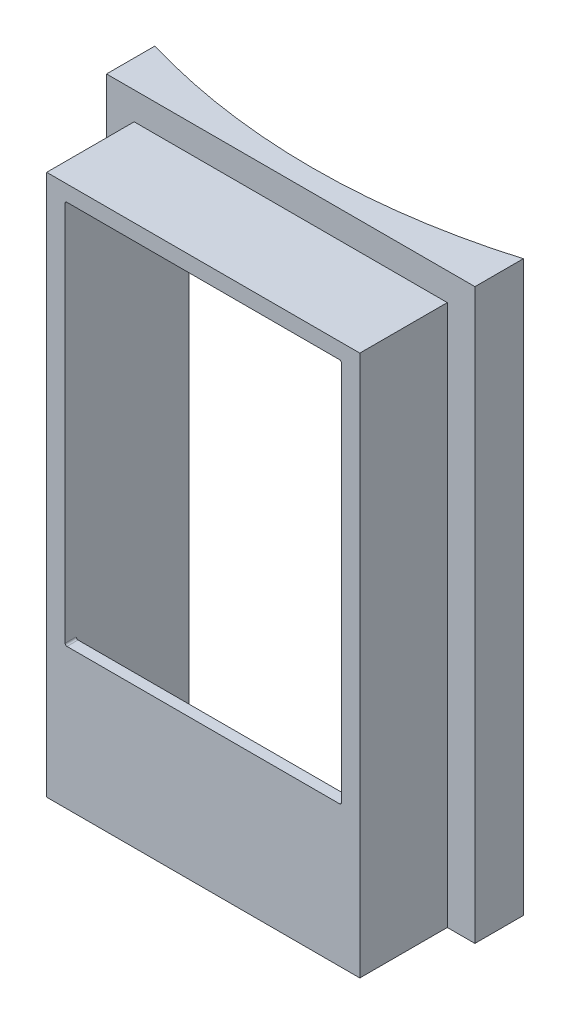
SolidWorks part; units mm, degrees
ref_plane "Front Plane" through (0, 0, 0) normal (0, 0, 1) x (1, 0, 0)
ref_plane "Top Plane" through (0, 0, 0) normal (0, 1, 0) x (1, 0, 0)
ref_plane "Right Plane" through (0, 0, 0) normal (1, 0, 0) x (0, 0, -1)
sketch "Sketch1" plane through (0, 0, 0) normal (0, 0, 1) x (1, 0, 0)
  line L1 (-63.5, 95.885) -> (63.5, 95.885)
  line L2 (-63.5, 95.885) -> (-63.5, -100.203)
  line L3 (-63.5, -100.203) -> (63.5, -100.203)
  line L4 (63.5, 95.885) -> (63.5, -100.203)
  point P5 (0, 95.885)
  dimension "D1" = 127
  dimension "D2" = 196.088
extrude "Extrude1" add sketch "Sketch1" along normal blind 230.2002
sketch "Sketch5" plane through (0, 0, 230.2002) normal (0, 0, 1) x (1, 0, 0)
  line L0 (63.5, 95.885) -> (-63.5, 95.885) construction
  line L1 (-53.975, 86.36) -> (53.975, 86.36)
  line L2 (-53.975, 86.36) -> (-53.975, -100.203)
  line L3 (-53.975, -100.203) -> (53.975, -100.203)
  line L4 (53.975, 86.36) -> (53.975, -100.203)
  line L5 (0, 95.885) -> (0, -100.203) construction
  line L8 (-63.5, -100.203) -> (63.5, -100.203) construction
  point P4 (0, -100.203)
  point P5 (0, 95.885)
  point P11 (0, 86.36)
  dimension "D1" = 107.95
  dimension "D2" = 9.525
extrude "Extrude4" add sketch "Sketch5" along normal blind 30.1523
sketch "Sketch2" plane through (0, 95.885, 0) normal (0, 1, 0) x (-1, 0, 0)
  line L0 (-63.5, 0) -> (63.5, 0) construction
  circle A1 centre (0, 0) radius 222.758
sketch "Sketch4" plane through (0, 0, 230.2002) normal (0, 0, 1) x (1, 0, 0)
  line L0 (53.975, 86.36) -> (-53.975, 86.36) construction
  line L1 (-47.625, 80.899) -> (47.625, 80.899)
  line L2 (-47.625, 80.899) -> (-47.625, -51.689)
  line L3 (-47.625, -51.689) -> (47.625, -51.689)
  line L4 (47.625, 80.899) -> (47.625, -51.689)
  point P4 (0, -51.689)
  point P5 (0, 80.899)
  point P6 (0, 0)
  dimension "D1" = 95.25
  dimension "D2" = 5.461
  dimension "D3" = 132.588
extrude "Extrude2" cut sketch "Sketch4" against normal blind 273.8502 and the other way blind 93.98
sketch "Sketch6" plane through (0, 0, 0) normal (0, 0, -1) x (-1, 0, 0)
  line L0 (-47.625, -51.689) -> (47.625, -51.689) construction
  line L1 (-47.625, -51.689) -> (47.625, -51.689)
  line L2 (-47.625, -51.689) -> (-47.625, -97.663)
  line L3 (-47.625, -97.663) -> (47.625, -97.663)
  line L4 (47.625, -51.689) -> (47.625, -97.663)
  line L6 (-47.625, 80.899) -> (47.625, 80.899)
  line L7 (-47.625, 80.899) -> (-47.625, 83.82)
  line L8 (-47.625, 83.82) -> (47.625, 83.82)
  line L9 (47.625, 80.899) -> (47.625, 83.82)
  line L10 (63.5, -100.203) -> (-63.5, -100.203) construction
  line L11 (-63.5, 95.885) -> (63.5, 95.885) construction
  point P4 (0, -100.203)
  point P6 (0, -51.689)
  point P13 (0, -100.203)
  point P15 (0, 95.885)
  point P19 (0, 80.899)
  point P22 (0, -97.663)
  dimension "D1" = 95.25
  dimension "D2" = 2.921
extrude "Extrude5" cut sketch "Sketch6" against normal blind 256.54
fillet "Fillet1" radius 2.54 4 edges at (-47.625, -97.663, 128.27) (47.625, -97.663, 128.27) (-47.625, 83.82, 128.27) (47.625, 83.82, 128.27)
extrude "Extrude3" cut sketch "Sketch2" against normal blind 202.86
sketch "Sketch7" plane through (0, 0, 260.3525) normal (0, 0, 1) x (1, 0, 0)
fillet "Fillet2" radius 0.635 4 edges at (47.625, 80.899, 258.4463) (-47.625, 80.899, 258.4463) (-47.625, -51.689, 258.4463) (47.625, -51.689, 258.4463)
sketch "Sketch8" plane through (0, 0, 260.3525) normal (0, 0, 1) x (1, 0, 0)
